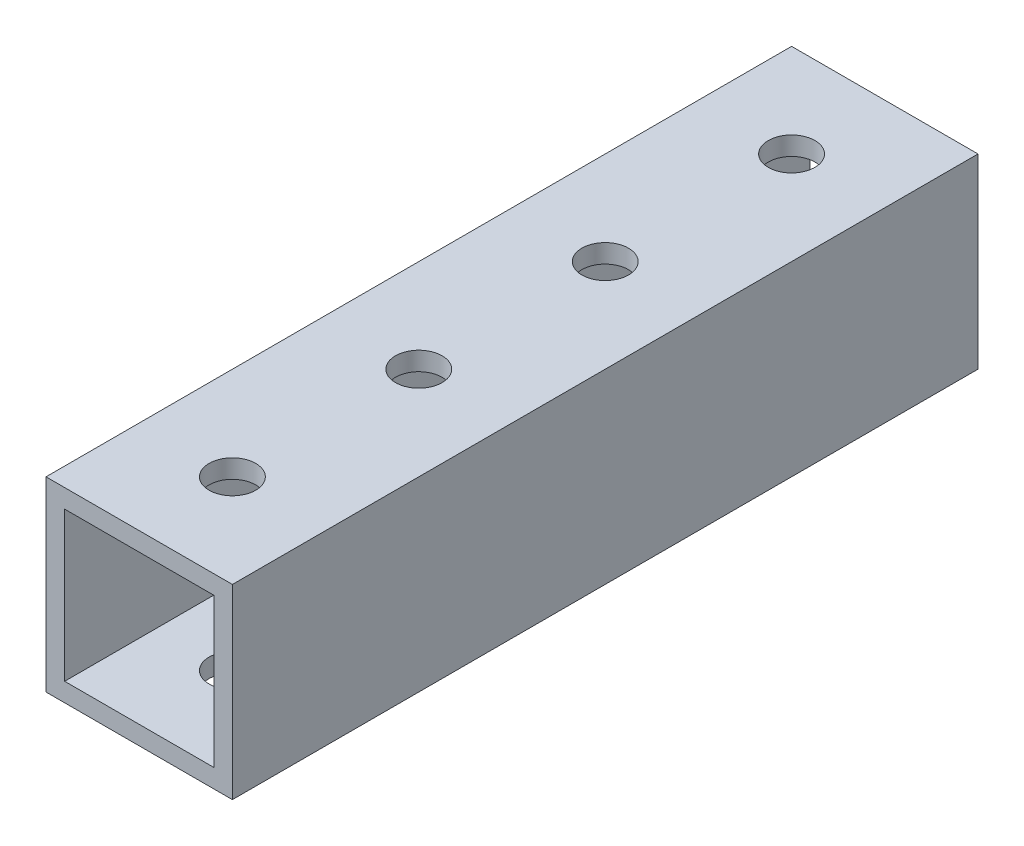
SolidWorks part; units mm, degrees
material "1345 Alloy"
ref_plane "Front Plane" through (0, 0, 0) normal (0, 0, 1) x (1, 0, 0)
ref_plane "Top Plane" through (0, 0, 0) normal (0, 1, 0) x (1, 0, 0)
ref_plane "Right Plane" through (0, 0, 0) normal (1, 0, 0) x (0, 0, -1)
sketch "Sketch1" plane through (0, 0, 0) normal (0, 0, 1) x (1, 0, 0)
  line L1 (-10, 10) -> (10, 10)
  line L2 (-10, 10) -> (-10, -10)
  line L3 (-10, -10) -> (10, -10)
  line L4 (10, 10) -> (10, -10)
  line L5 (-10, 10) -> (10, -10) construction
  line L6 (-10, -10) -> (10, 10) construction
  line L7 (-8, 8) -> (8, 8)
  line L8 (-8, 8) -> (-8, -8)
  line L9 (-8, -8) -> (8, -8)
  line L10 (8, 8) -> (8, -8)
  line L11 (-8, 8) -> (8, -8) construction
  line L12 (-8, -8) -> (8, 8) construction
  point P0 (0, 0)
  point P6 (0, 0)
  dimension "D1" = 20
  dimension "D2" = 20
  dimension "D3" = 16
extrude "Boss-Extrude1" add sketch "Sketch1" along normal blind 80
sketch "Sketch2" plane through (0, 10, 0) normal (0, 1, 0) x (1, 0, 0)
  line L0 (0, 6.4671) -> (0, -187.4374) construction
  line L1 (10, 0) -> (-10, 0) construction
  line L2 (-10, -40) -> (10, -40) construction
  line L3 (-10, -80) -> (-10, 0) construction
  line L4 (10, -80) -> (10, 0) construction
  circle A0 centre (0, -10) radius 2.5
  circle A1 centre (0, -30) radius 2.5
  circle A2 centre (0, -50) radius 2.5
  circle A3 centre (0, -70) radius 2.5
  dimension "D1" = 5
  dimension "D2" = 5
  dimension "D3" = 20
  dimension "D4" = 10
extrude "Cut-Extrude1" cut sketch "Sketch2" against normal through all
